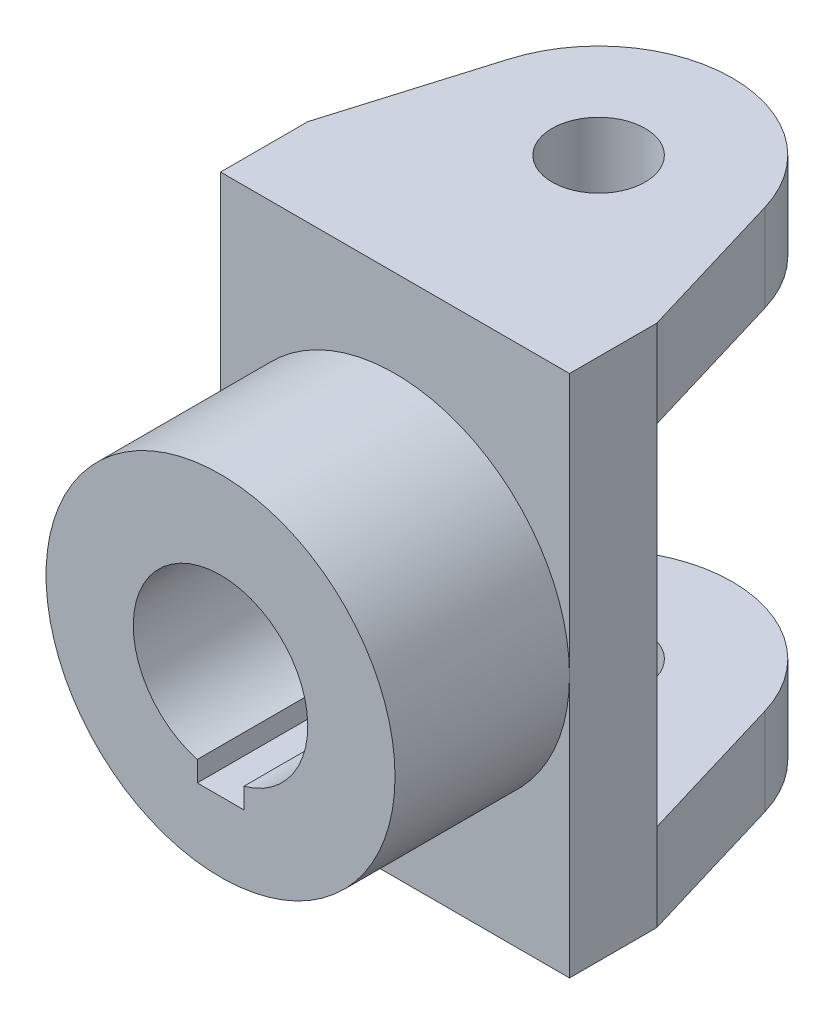
SolidWorks part; units mm, degrees
ref_plane "Front Plane" through (0, 0, 0) normal (0, 0, 1) x (1, 0, 0)
ref_plane "Top Plane" through (0, 0, 0) normal (0, 1, 0) x (1, 0, 0)
ref_plane "Right Plane" through (0, 0, 0) normal (1, 0, 0) x (0, 0, -1)
sketch "Sketch1" plane through (0, 0, 0) normal (0, 0, 1) x (1, 0, 0)
  line L0 (0, 0) -> (0, 68.7916) construction
  line L2 (-4, -14.4568) -> (-4, -17.9568)
  line L3 (-4, -17.9568) -> (4, -17.9568)
  line L4 (4, -14.4568) -> (4, -17.9568)
  circle A0 centre (0, 0) radius 30
  arc A1 (4, -14.4568) -> (-4, -14.4568) centre (0, 0) ccw
  dimension "D1" = 60
  dimension "D2" = 30
  dimension "D3" = 3.5
  dimension "D4" = 8
extrude "Boss-Extrude1" add sketch "Sketch1" against normal blind 30
sketch "Sketch2" plane through (0, 0, -30) normal (0, 0, -1) x (-1, 0, 0)
  line L1 (30, 45) -> (-30, 45)
  line L2 (30, 45) -> (30, -45)
  line L3 (30, -45) -> (-30, -45)
  line L4 (-30, 45) -> (-30, -45)
  line L5 (30, 45) -> (-30, -45) construction
  line L6 (30, -45) -> (-30, 45) construction
  point P0 (0, 0)
  dimension "D1" = 90
  dimension "D2" = 60
extrude "Boss-Extrude2" add sketch "Sketch2" along normal blind 15
sketch "Sketch3" plane through (0, 45, 0) normal (0, 1, 0) x (1, 0, 0)
  line L0 (-30, 30) -> (30, 30) construction
  line L1 (22.0329, 71.5993) -> (30, 45)
  line L2 (30, 45) -> (30, 30)
  line L3 (30, 30) -> (-30, 30)
  line L4 (-30, 30) -> (-30, 45)
  line L5 (-30, 45) -> (-22.0329, 71.5993)
  arc A0 (22.0329, 71.5993) -> (-22.0329, 71.5993) centre (0, 65) ccw
  circle A1 centre (0, 65) radius 8
  dimension "D1" = 46
  dimension "D2" = 16
  dimension "D3" = 35
extrude "Boss-Extrude3" add sketch "Sketch3" against normal blind 15
mirror "Mirror1" about plane through (0, 0, 0) normal (0, 1, 0) of "Boss-Extrude3"
